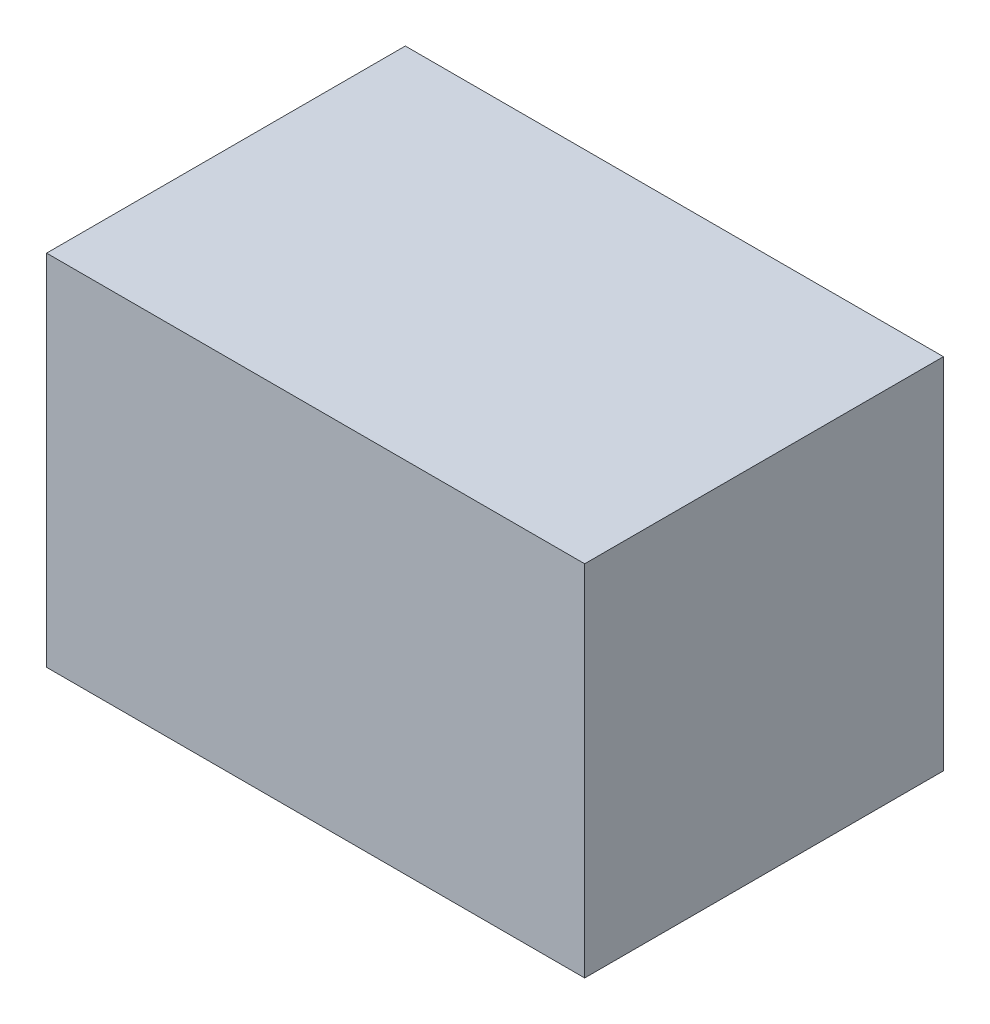
SolidWorks part; units mm, degrees
ref_plane "Front Plane" through (0, 0, 0) normal (0, 0, 1) x (1, 0, 0)
ref_plane "Top Plane" through (0, 0, 0) normal (0, 1, 0) x (1, 0, 0)
ref_plane "Right Plane" through (0, 0, 0) normal (1, 0, 0) x (0, 0, -1)
other "Configuration Table"
sketch "Sketch1" plane through (0, 0, 0) normal (0, 0, 1) x (1, 0, 0)
  line L1 (100, 700) -> (130, 700)
  line L2 (100, 700) -> (100, 720)
  line L3 (100, 720) -> (130, 720)
  line L4 (130, 700) -> (130, 720)
extrude "PACK_kapak_switch_1_1" add sketch "Sketch1" against normal blind 20 from offset 620 separate body
